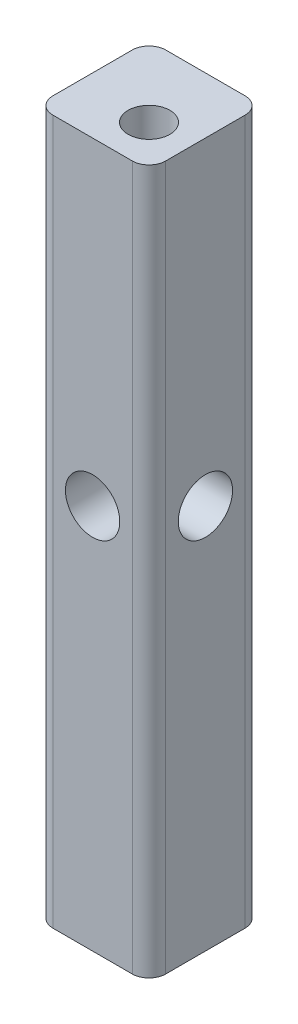
SolidWorks part; units mm, degrees
material "ABS"
ref_plane "Front Plane" through (0, 0, 0) normal (0, 0, 1) x (1, 0, 0)
ref_plane "Top Plane" through (0, 0, 0) normal (0, 1, 0) x (1, 0, 0)
ref_plane "Right Plane" through (0, 0, 0) normal (1, 0, 0) x (0, 0, -1)
sketch "Sketch4" plane through (0, 0, 0) normal (0, 1, 0) x (1, 0, 0)
  line L27 (0, 0) -> (-2.5, 0) construction
  line L55 (0, 0) -> (2.5, 0) construction
  line L56 (2.5, 0) -> (5, 0) construction
  line L61 (-2.5, 0) -> (-8.5, 0) construction
  line L62 (0, 0) -> (0, 2.5) construction
  line L63 (0, 2.5) -> (0, 8.5) construction
  line L64 (-8.5, 8.5) -> (5, 8.5)
  line L65 (5, 8.5) -> (5, -5)
  line L66 (5, -5) -> (-8.5, -5)
  line L67 (-8.5, -5) -> (-8.5, 8.5)
  line L68 (0, 0) -> (0, -2.5) construction
  line L69 (0, -2.5) -> (0, -5) construction
  circle A3 centre (0, 0) radius 2.5
  point P10 (0, 0)
  dimension "D2" = 5
  dimension "D1" = 6
  dimension "D3" = 2.5
extrude "hole-TopMain" add sketch "Sketch4" along normal up to surface (64.27 mm away)
ref_plane "Plane-Side" through (-3.5, 0, 0) normal (-1, 0, 0) x (0, 0, 1)
sketch "Sketch12" plane through (5, 0, 0) normal (1, 0, 0) x (0, 0, -1)
  line L0 (1.75, 26.5749) -> (1.75, 15.6051) construction
  line L2 (8.5, 64.27) -> (-5, 64.27) construction
  circle A0 centre (1.75, 46.135) radius 2.5
  circle A1 centre (1.75, 46.135) radius 2.5 construction
  point P1 (1.75, 64.27)
  dimension "D1" = 5
extrude "hole-Side1" cut sketch "Sketch12" against normal through all
sketch "Sketch13" plane through (-3.5, 0, 0) normal (-1, 0, 0) x (0, 0, 1)
  circle A0 centre (-1.75, 46.135) radius 3.25
  circle A1 centre (-1.75, 46.135) radius 2.5 construction
  dimension "D1" = 6.5
extrude "hole-Side2" cut sketch "Sketch13" against normal through all
ref_plane "Plane2" through (0, 0, -3.5) normal (0, 0, -1) x (-1, 0, 0)
sketch "Sketch14" plane through (0, 0, -8.5) normal (0, 0, -1) x (-1, 0, 0)
  line L0 (1.75, 66.1204) -> (1.75, -49933.8796) construction
  line L1 (8.5, 64.27) -> (-5, 64.27) construction
  circle A0 centre (1.75, 46.135) radius 2.5
  circle A1 centre (1.75, 46.135) radius 2.5 construction
  point P2 (1.75, 64.27)
  dimension "D1" = 5
extrude "Cut-Extrude9" cut sketch "Sketch14" against normal through all
sketch "Sketch15" plane through (0, 0, -3.5) normal (0, 0, -1) x (-1, 0, 0)
  circle A0 centre (1.75, 46.135) radius 3.25
  circle A1 centre (1.75, 46.135) radius 2.5 construction
  dimension "D1" = 6.5
extrude "Cut-Extrude10" cut sketch "Sketch15" against normal through all
fillet "Fillet3" radius 2 4 edges at (5, 32.135, -8.5) (5, 32.135, 5) (-8.5, 32.135, -8.5) (-8.5, 32.135, 5)
sketch "Sketch16" [suppressed] plane through (0, 64.27, 0) normal (0, 1, 0) x (1, 0, 0)
  line L0 (-6.5, 8.5) -> (3, 8.5)
  line L1 (-6.5, 8.5) -> (3, 8.5) construction
  line L2 (5, 6.5) -> (5, -3)
  line L3 (3, -5) -> (-6.5, -5)
  line L4 (-8.5, -3) -> (-8.5, 6.5)
  arc A0 (-6.5, 8.5) -> (-8.5, 6.5) centre (-6.5, 6.5) ccw construction
  arc A1 (-8.5, 6.5) -> (-6.5, 8.5) centre (-6.5, 6.5) cw
  arc A2 (3, 8.5) -> (5, 6.5) centre (3, 6.5) cw
  arc A3 (5, -3) -> (3, -5) centre (3, -3) cw
  arc A4 (-6.5, -5) -> (-8.5, -3) centre (-6.5, -3) cw
  circle A5 centre (0, 0) radius 2.5
extrude "Boss-Extrude1" [suppressed] add sketch "Sketch16" along normal blind 20
sketch "Sketch17" plane through (0, 64.27, 0) normal (0, 1, 0) x (1, 0, 0)
  line L0 (-8.5, 6.5) -> (-8.5, -3)
  line L1 (-8.5, -3) -> (-8.5, 6.5) construction
  line L2 (-6.5, -5) -> (3, -5)
  line L3 (5, -3) -> (5, 6.5)
  line L4 (3, 8.5) -> (-6.5, 8.5)
  arc A0 (-8.5, -3) -> (-6.5, -5) centre (-6.5, -3) ccw construction
  arc A1 (5, 6.5) -> (3, 8.5) centre (3, 6.5) ccw construction
  arc A2 (-6.5, 8.5) -> (-8.5, 6.5) centre (-6.5, 6.5) ccw
  arc A3 (5, -3) -> (3, -5) centre (3, -3) cw
  arc A4 (5, 6.5) -> (3, 8.5) centre (3, 6.5) ccw
  arc A5 (-8.5, -3) -> (-6.5, -5) centre (-6.5, -3) ccw
  circle A6 centre (0, 0) radius 2.5
extrude "Boss-Extrude2" add sketch "Sketch17" along normal blind 20
equation "\"tolerance\"= 0.1mm"
